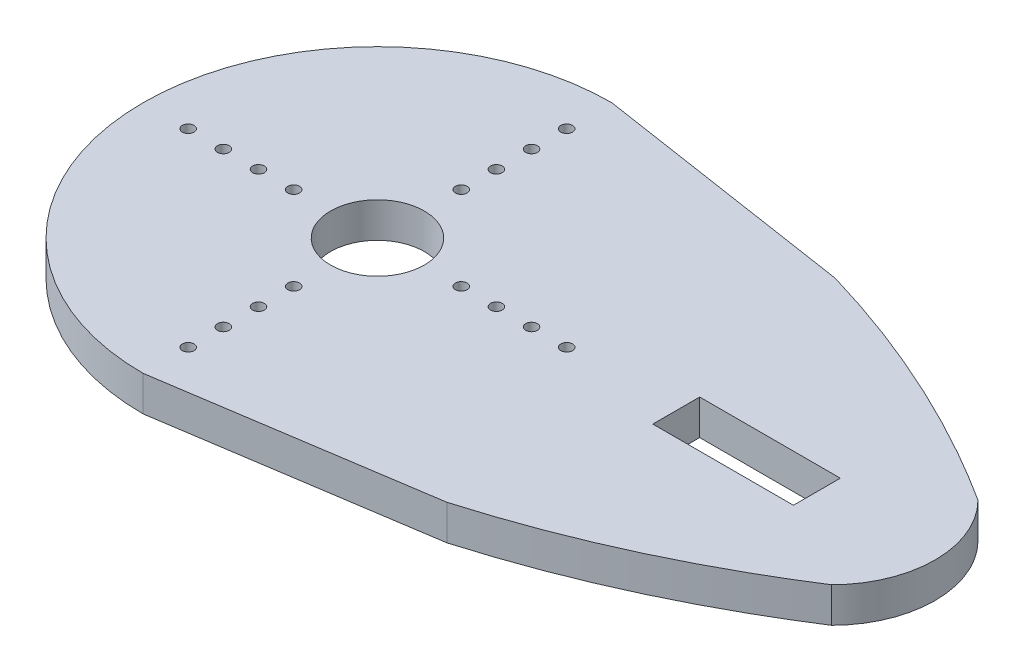
SolidWorks part; units mm, degrees
ref_plane "Front Plane" through (0, 0, 0) normal (0, 0, 1) x (1, 0, 0)
ref_plane "Top Plane" through (0, 0, 0) normal (0, 1, 0) x (1, 0, 0)
ref_plane "Right Plane" through (0, 0, 0) normal (1, 0, 0) x (0, 0, -1)
sketch "Sketch1" plane through (0, 0, 0) normal (0, 1, 0) x (1, 0, 0)
  line L0 (0, -20) -> (0, 20)
  line L1 (0, 20) -> (45, 20)
  line L2 (45, 6.25) -> (45, -6.25)
  line L3 (0, 0) -> (45, 0)
  line L4 (45, 6.25) -> (45, 20)
  line L5 (0, 20) -> (45, 13.125)
  line L6 (45, -6.25) -> (45, -20)
  line L7 (0, -20) -> (45, -13.125)
  line L8 (45, -3.8383) -> (31.5, -3.8383)
  line L9 (0, 0) -> (-7.15, 0)
  line L10 (25.5, 2) -> (37.5, 2)
  line L11 (25.5, 2) -> (25.5, -2)
  line L12 (25.5, -2) -> (37.5, -2)
  line L13 (37.5, 2) -> (37.5, -2)
  line L14 (25.5, 2) -> (37.5, -2) construction
  line L15 (25.5, -2) -> (37.5, 2) construction
  line L16 (-7.15, 0) -> (-10.15, 0)
  line L17 (-10.15, 0) -> (-13.15, 0)
  line L18 (-13.15, 0) -> (-16.15, 0)
  line L19 (0, 10.15) -> (0, 13.15)
  line L20 (0, 13.15) -> (0, 16.15)
  line L21 (0, 7.15) -> (0, 10.15)
  line L22 (0, 0) -> (0, 7.15)
  line L23 (10.15, 0) -> (13.15, 0)
  line L24 (13.15, 0) -> (16.15, 0)
  line L25 (7.15, 0) -> (10.15, 0)
  line L26 (0, 0) -> (7.15, 0)
  line L27 (0, -10.15) -> (0, -13.15)
  line L28 (0, -13.15) -> (0, -16.15)
  line L29 (0, -7.15) -> (0, -10.15)
  line L30 (0, 0) -> (0, -7.15)
  arc A0 (0, 20) -> (0, -20) centre (0, 0) ccw
  arc A1 (45, 6.25) -> (45, -6.25) centre (38.75, 0) cw
  circle A5 centre (-16.15, 0) radius 0.5
  circle A6 centre (-13.15, 0) radius 0.5
  circle A7 centre (-10.15, 0) radius 0.5
  circle A8 centre (-7.15, 0) radius 0.5
  circle A9 centre (0, 0) radius 4
  circle A10 centre (0, 10.15) radius 0.5
  circle A11 centre (0, 13.15) radius 0.5
  circle A12 centre (0, 16.15) radius 0.5
  circle A13 centre (0, 7.15) radius 0.5
  circle A14 centre (10.15, 0) radius 0.5
  circle A15 centre (13.15, 0) radius 0.5
  circle A16 centre (16.15, 0) radius 0.5
  circle A17 centre (7.15, 0) radius 0.5
  circle A18 centre (0, -10.15) radius 0.5
  circle A19 centre (0, -13.15) radius 0.5
  circle A20 centre (0, -16.15) radius 0.5
  circle A21 centre (0, -7.15) radius 0.5
  spline S0 degree 2 poles (0, 20) (24.3878, 19.4353) (45, 6.25) knots 0 0 0 1 1 1
  spline S1 degree 2 poles (0, -20) (24.3878, -19.4353) (45, -6.25) knots 0 0 0 1 1 1
  point P16 (31.5, 0)
  point P57 (0, 0)
  dimension "D10" = 8
  dimension "D8" = 1
  dimension "D1" = 40
  dimension "D2" = 45
  dimension "D3" = 12.5
  dimension "D4" = 13.5
  dimension "D5" = 12
  dimension "D6" = 4
  dimension "D7" = 3
  dimension "D9" = 7.15
  dimension "D11" = 4
extrude "Boss-Extrude1" add sketch "Sketch1" along normal blind 3
